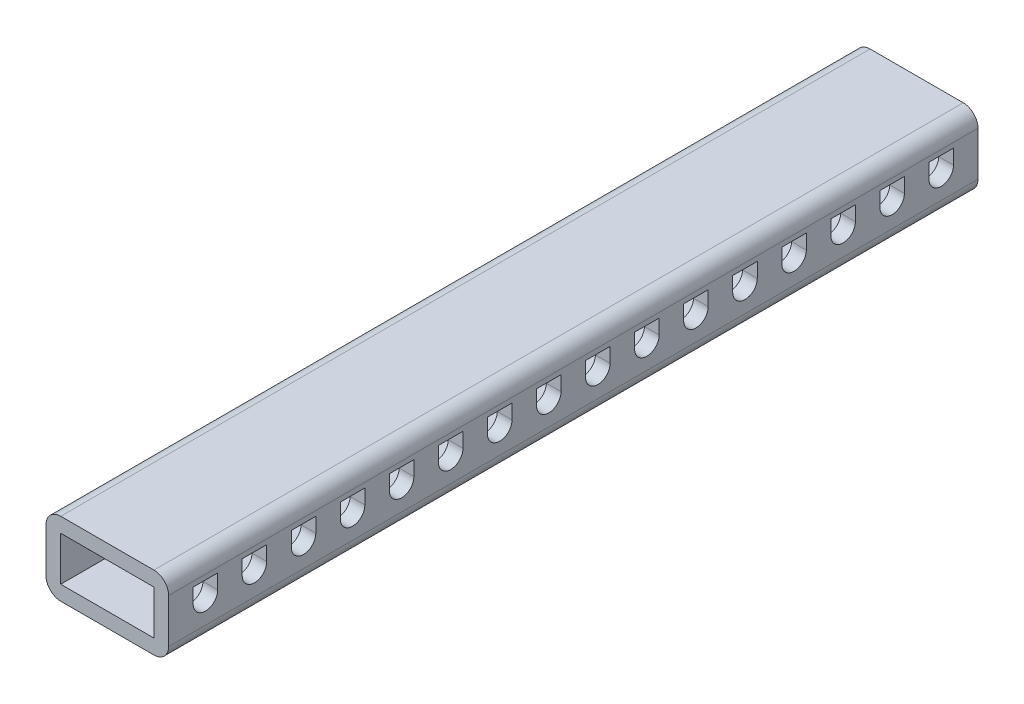
SolidWorks part; units mm, degrees
ref_plane "Front Plane" through (0, 0, 0) normal (0, 0, 1) x (1, 0, 0)
ref_plane "Top Plane" through (0, 0, 0) normal (0, 1, 0) x (1, 0, 0)
ref_plane "Right Plane" through (0, 0, 0) normal (1, 0, 0) x (0, 0, -1)
sketch "Sketch1" plane through (0, 0, 0) normal (0, 0, 1) x (1, 0, 0)
  line L1 (-12.5, 7.5) -> (12.5, 7.5)
  line L2 (-12.5, 7.5) -> (-12.5, -7.5)
  line L3 (-12.5, -7.5) -> (12.5, -7.5)
  line L4 (12.5, 7.5) -> (12.5, -7.5)
  line L5 (-12.5, 7.5) -> (12.5, -7.5) construction
  line L6 (-12.5, -7.5) -> (12.5, 7.5) construction
  point P0 (0, 0)
  dimension "D1" = 25
  dimension "D2" = 15
extrude "Boss-Extrude1" add sketch "Sketch1" along normal blind 165
sketch "Sketch2" plane through (0, 0, 165) normal (0, 0, 1) x (1, 0, 0)
  line L0 (-12.5, 7.5) -> (-12.5, -7.5) construction
  line L1 (-9.5, -4.5) -> (9.5, -4.5)
  line L2 (-9.5, -4.5) -> (-9.5, 4.5)
  line L3 (-9.5, 4.5) -> (9.5, 4.5)
  line L4 (9.5, -4.5) -> (9.5, 4.5)
  line L5 (-9.5, -4.5) -> (9.5, 4.5) construction
  line L6 (-9.5, 4.5) -> (9.5, -4.5) construction
  line L7 (12.5, 7.5) -> (-12.5, 7.5) construction
  point P0 (0, 0)
  dimension "D1" = 3
  dimension "D2" = 3
extrude "Cut-Extrude1" cut sketch "Sketch2" against normal blind 263
sketch "Sketch3" plane through (12.5, 0, 0) normal (1, 0, 0) x (0, 0, -1)
  line L1 (-165, 7.5) -> (0, 7.5) construction
  line L2 (-160, 3.5) -> (-155, 3.5)
  line L3 (-160, 3.5) -> (-160, 0.5)
  line L5 (-155, 3.5) -> (-155, 0.5)
  line L6 (-165, -7.5) -> (-165, 7.5) construction
  line L7 (-152.5, 7.5) -> (-152.5, 3.8883) construction
  line L8 (-150, 3.5) -> (-150, 0.5)
  line L9 (-145, 3.5) -> (-145, 0.5)
  line L10 (-145, 3.5) -> (-150, 3.5)
  line L11 (-142.5, 7.5) -> (-142.5, 3.8883) construction
  line L12 (-132.5, 7.5) -> (-132.5, 3.8883) construction
  line L13 (-140, 3.5) -> (-135, 3.5)
  line L14 (-140, 3.5) -> (-140, 0.5)
  line L15 (-135, 3.5) -> (-135, 0.5)
  line L16 (-130, 3.5) -> (-130, 0.5)
  line L17 (-125, 3.5) -> (-125, 0.5)
  line L18 (-125, 3.5) -> (-130, 3.5)
  line L19 (-122.5, 7.5) -> (-122.5, 3.8883) construction
  line L20 (-112.5, 7.5) -> (-112.5, 3.8883) construction
  line L21 (-130, 3.5) -> (-130, 0.5)
  line L22 (-125, 3.5) -> (-125, 0.5)
  line L23 (-125, 3.5) -> (-130, 3.5)
  line L24 (-120, 3.5) -> (-115, 3.5)
  line L25 (-120, 3.5) -> (-120, 0.5)
  line L26 (-115, 3.5) -> (-115, 0.5)
  line L27 (-110, 3.5) -> (-110, 0.5)
  line L28 (-105, 3.5) -> (-105, 0.5)
  line L29 (-105, 3.5) -> (-110, 3.5)
  line L30 (-102.5, 7.5) -> (-102.5, 3.8883) construction
  line L31 (-92.5, 7.5) -> (-92.5, 3.8883) construction
  line L32 (-82.5, 7.5) -> (-82.5, 3.8883) construction
  line L33 (-72.5, 7.5) -> (-72.5, 3.8883) construction
  line L34 (-110, 3.5) -> (-110, 0.5)
  line L35 (-105, 3.5) -> (-105, 0.5)
  line L36 (-105, 3.5) -> (-110, 3.5)
  line L37 (-100, 3.5) -> (-95, 3.5)
  line L38 (-100, 3.5) -> (-100, 0.5)
  line L39 (-95, 3.5) -> (-95, 0.5)
  line L40 (-100, 3.5) -> (-95, 3.5)
  line L41 (-100, 3.5) -> (-100, 0.5)
  line L42 (-95, 3.5) -> (-95, 0.5)
  line L43 (-90, 3.5) -> (-90, 0.5)
  line L44 (-85, 3.5) -> (-85, 0.5)
  line L45 (-85, 3.5) -> (-90, 3.5)
  line L46 (-80, 3.5) -> (-75, 3.5)
  line L47 (-80, 3.5) -> (-80, 0.5)
  line L48 (-75, 3.5) -> (-75, 0.5)
  line L49 (-70, 3.5) -> (-70, 0.5)
  line L50 (-65, 3.5) -> (-65, 0.5)
  line L51 (-65, 3.5) -> (-70, 3.5)
  line L52 (-62.5, 7.5) -> (-62.5, 3.8883) construction
  line L53 (-52.5, 7.5) -> (-52.5, 3.8883) construction
  line L54 (-42.5, 7.5) -> (-42.5, 3.8883) construction
  line L55 (-32.5, 7.5) -> (-32.5, 3.8883) construction
  line L56 (-22.5, 7.5) -> (-22.5, 3.8883) construction
  line L57 (-12.5, 7.5) -> (-12.5, 3.8883) construction
  line L58 (-2.5, 7.5) -> (-2.5, 3.8883) construction
  line L59 (7.5, 7.5) -> (7.5, 3.8883) construction
  line L60 (-70, 3.5) -> (-70, 0.5)
  line L61 (-65, 3.5) -> (-65, 0.5)
  line L62 (-65, 3.5) -> (-70, 3.5)
  line L63 (-60, 3.5) -> (-55, 3.5)
  line L64 (-60, 3.5) -> (-60, 0.5)
  line L65 (-55, 3.5) -> (-55, 0.5)
  line L66 (-50, 3.5) -> (-50, 0.5)
  line L67 (-45, 3.5) -> (-45, 0.5)
  line L68 (-45, 3.5) -> (-50, 3.5)
  line L69 (-50, 3.5) -> (-50, 0.5)
  line L70 (-45, 3.5) -> (-45, 0.5)
  line L71 (-45, 3.5) -> (-50, 3.5)
  line L72 (-40, 3.5) -> (-35, 3.5)
  line L73 (-40, 3.5) -> (-40, 0.5)
  line L74 (-35, 3.5) -> (-35, 0.5)
  line L75 (-40, 3.5) -> (-35, 3.5)
  line L76 (-40, 3.5) -> (-40, 0.5)
  line L77 (-35, 3.5) -> (-35, 0.5)
  line L78 (-30, 3.5) -> (-30, 0.5)
  line L79 (-25, 3.5) -> (-25, 0.5)
  line L80 (-25, 3.5) -> (-30, 3.5)
  line L81 (-20, 3.5) -> (-15, 3.5)
  line L82 (-20, 3.5) -> (-20, 0.5)
  line L83 (-15, 3.5) -> (-15, 0.5)
  line L84 (-20, 3.5) -> (-15, 3.5)
  line L85 (-20, 3.5) -> (-20, 0.5)
  line L86 (-15, 3.5) -> (-15, 0.5)
  line L87 (-10, 3.5) -> (-10, 0.5)
  line L88 (-5, 3.5) -> (-5, 0.5)
  line L89 (-5, 3.5) -> (-10, 3.5)
  line L90 (0, 3.5) -> (5, 3.5)
  line L91 (0, 3.5) -> (0, 0.5)
  line L92 (5, 3.5) -> (5, 0.5)
  line L93 (10, 3.5) -> (10, 0.5)
  line L94 (15, 3.5) -> (15, 0.5)
  line L95 (15, 3.5) -> (10, 3.5)
  line L96 (10, 3.5) -> (10, 0.5)
  line L97 (40, 3.5) -> (45, 3.5)
  line L98 (40, 3.5) -> (40, 0.5)
  line L99 (45, 3.5) -> (45, 0.5)
  line L100 (17.5, 7.5) -> (17.5, 3.8883) construction
  line L101 (27.5, 7.5) -> (27.5, 3.8883) construction
  line L102 (37.5, 7.5) -> (37.5, 3.8883) construction
  line L103 (15, 3.5) -> (15, 0.5)
  line L104 (15, 3.5) -> (10, 3.5)
  line L105 (20, 3.5) -> (25, 3.5)
  line L106 (20, 3.5) -> (20, 0.5)
  line L107 (25, 3.5) -> (25, 0.5)
  line L108 (30, 3.5) -> (30, 0.5)
  line L109 (35, 3.5) -> (35, 0.5)
  line L110 (35, 3.5) -> (30, 3.5)
  line L111 (30, 3.5) -> (30, 0.5)
  line L112 (35, 3.5) -> (35, 0.5)
  line L113 (35, 3.5) -> (30, 3.5)
  line L114 (47.5, 7.5) -> (47.5, 3.8883) construction
  line L115 (40, 3.5) -> (45, 3.5)
  line L116 (40, 3.5) -> (40, 0.5)
  line L117 (45, 3.5) -> (45, 0.5)
  line L118 (40, 3.5) -> (45, 3.5)
  line L119 (40, 3.5) -> (40, 0.5)
  line L120 (45, 3.5) -> (45, 0.5)
  line L121 (50, 3.5) -> (50, 0.5)
  line L122 (55, 3.5) -> (55, 0.5)
  line L123 (55, 3.5) -> (50, 3.5)
  arc A0 (-160, 0.5) -> (-155, 0.5) centre (-157.5, 0.5) ccw
  arc A1 (-145, 0.5) -> (-150, 0.5) centre (-147.5, 0.5) cw
  arc A2 (-140, 0.5) -> (-135, 0.5) centre (-137.5, 0.5) ccw
  arc A3 (-125, 0.5) -> (-130, 0.5) centre (-127.5, 0.5) cw
  arc A4 (-125, 0.5) -> (-130, 0.5) centre (-127.5, 0.5) cw
  arc A5 (-120, 0.5) -> (-115, 0.5) centre (-117.5, 0.5) ccw
  arc A6 (-105, 0.5) -> (-110, 0.5) centre (-107.5, 0.5) cw
  arc A7 (-105, 0.5) -> (-110, 0.5) centre (-107.5, 0.5) cw
  arc A8 (-100, 0.5) -> (-95, 0.5) centre (-97.5, 0.5) ccw
  arc A9 (-100, 0.5) -> (-95, 0.5) centre (-97.5, 0.5) ccw
  arc A10 (-85, 0.5) -> (-90, 0.5) centre (-87.5, 0.5) cw
  arc A11 (-80, 0.5) -> (-75, 0.5) centre (-77.5, 0.5) ccw
  arc A12 (-65, 0.5) -> (-70, 0.5) centre (-67.5, 0.5) cw
  arc A13 (-65, 0.5) -> (-70, 0.5) centre (-67.5, 0.5) cw
  arc A14 (-60, 0.5) -> (-55, 0.5) centre (-57.5, 0.5) ccw
  arc A15 (-45, 0.5) -> (-50, 0.5) centre (-47.5, 0.5) cw
  arc A16 (-45, 0.5) -> (-50, 0.5) centre (-47.5, 0.5) cw
  arc A17 (-40, 0.5) -> (-35, 0.5) centre (-37.5, 0.5) ccw
  arc A18 (-40, 0.5) -> (-35, 0.5) centre (-37.5, 0.5) ccw
  arc A19 (-25, 0.5) -> (-30, 0.5) centre (-27.5, 0.5) cw
  arc A20 (-20, 0.5) -> (-15, 0.5) centre (-17.5, 0.5) ccw
  arc A21 (-20, 0.5) -> (-15, 0.5) centre (-17.5, 0.5) ccw
  arc A22 (-5, 0.5) -> (-10, 0.5) centre (-7.5, 0.5) cw
  arc A23 (0, 0.5) -> (5, 0.5) centre (2.5, 0.5) ccw
  arc A24 (15, 0.5) -> (10, 0.5) centre (12.5, 0.5) cw
  arc A25 (40, 0.5) -> (45, 0.5) centre (42.5, 0.5) ccw
  arc A26 (15, 0.5) -> (10, 0.5) centre (12.5, 0.5) cw
  arc A27 (20, 0.5) -> (25, 0.5) centre (22.5, 0.5) ccw
  arc A28 (35, 0.5) -> (30, 0.5) centre (32.5, 0.5) cw
  arc A29 (35, 0.5) -> (30, 0.5) centre (32.5, 0.5) cw
  arc A30 (40, 0.5) -> (45, 0.5) centre (42.5, 0.5) ccw
  arc A31 (40, 0.5) -> (45, 0.5) centre (42.5, 0.5) ccw
  arc A32 (55, 0.5) -> (50, 0.5) centre (52.5, 0.5) cw
  point P18 (-145, 2)
  dimension "D1" = 4
  dimension "D2" = 5
  dimension "D3" = 5
  dimension "D4" = 3
  dimension "D5" = 5
  dimension "D6" = 5
extrude "Cut-Extrude2" cut sketch "Sketch3" against normal blind 263 contours L3 A0 L5 L2 | A1 L9 L10 L8 | L14 A2 L15 L13 | A3 L17 L18 L16 | L25 A5 L26 L24 | A6 L28 L29 L27 | L38 A8 L39 L37 | A10 L44 L45 L43 | L47 A11 L48 L46 | A12 L50 L51 L49 | L64 A14 L65 L63 | A15 L67 L68 L66 | L73 A17 L74 L72 | A19 L79 L80 L78 | L82 A20 L83 L81 | A22 L88 L89 L87 | L91 A23 L92 L90 | A24 L94 L95 L93 | L106 A27 L107 L105 | A28 L109 L110 L108 | L98 A25 L99 L97 | A32 L122 L123 L121
fillet "Fillet1" radius 3 4 edges at (-12.5, -7.5, 82.5) (12.5, -7.5, 82.5) (12.5, 7.5, 82.5) (-12.5, 7.5, 82.5)
